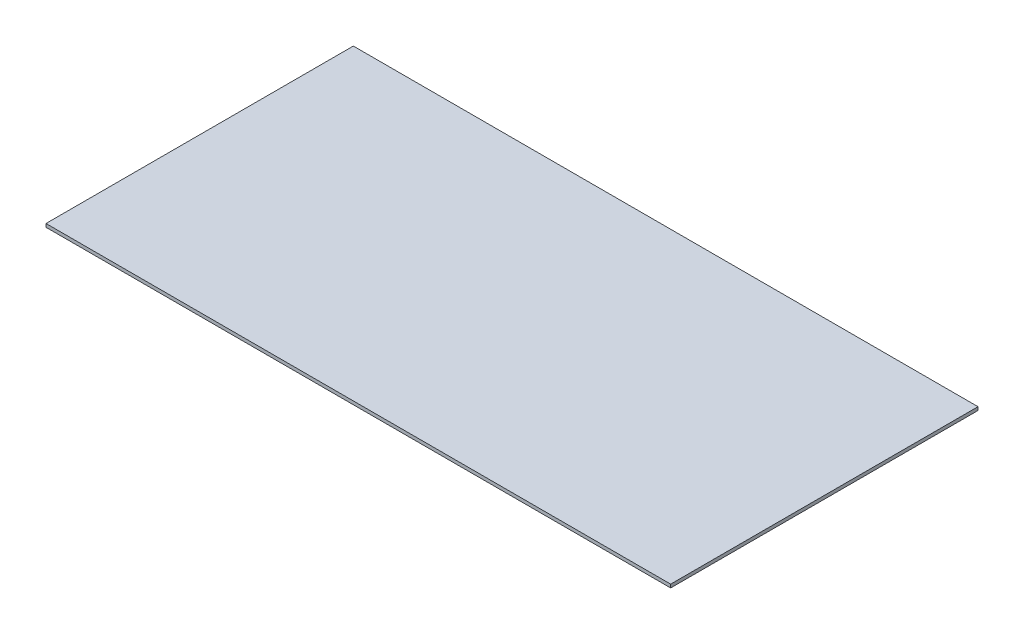
SolidWorks part; units mm, degrees
material "Glass"
ref_plane "Front Plane" through (0, 0, 0) normal (0, 0, 1) x (1, 0, 0)
ref_plane "Top Plane" through (0, 0, 0) normal (0, 1, 0) x (1, 0, 0)
ref_plane "Right Plane" through (0, 0, 0) normal (1, 0, 0) x (0, 0, -1)
sketch "Sketch1" plane through (0, 0, 0) normal (0, 1, 0) x (1, 0, 0)
  line L1 (0, 0) -> (563, 0)
  line L2 (0, 0) -> (0, 277)
  line L3 (0, 277) -> (563, 277)
  line L4 (563, 0) -> (563, 277)
  dimension "D1" = 277
  dimension "D2" = 563
extrude "Boss-Extrude1" add sketch "Sketch1" along normal blind 3
